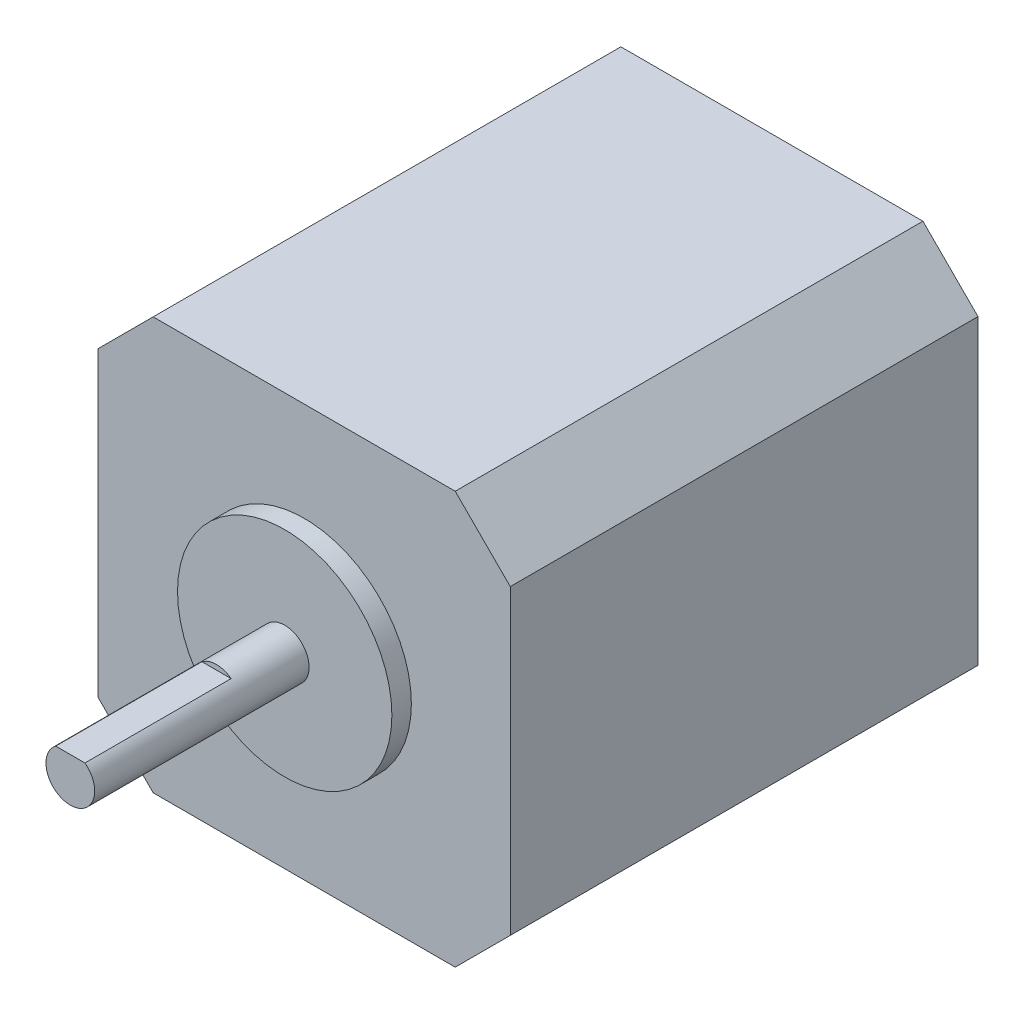
SolidWorks part; units mm, degrees
ref_plane "Front Plane" through (0, 0, 0) normal (0, 0, 1) x (1, 0, 0)
ref_plane "Top Plane" through (0, 0, 0) normal (0, 1, 0) x (1, 0, 0)
ref_plane "Right Plane" through (0, 0, 0) normal (1, 0, 0) x (0, 0, -1)
sketch "Sketch2" plane through (0, 0, 0) normal (0, 0, 1) x (1, 0, 0)
  line L1 (5.65, 0) -> (36.65, 0)
  line L2 (0, 5.65) -> (0, 36.65)
  line L3 (5.65, 42.3) -> (36.65, 42.3)
  line L4 (42.3, 5.65) -> (42.3, 36.65)
  line L5 (36.65, 0) -> (42.3, 5.65)
  line L6 (0, 5.65) -> (5.65, 0)
  line L7 (0, 36.65) -> (5.65, 42.3)
  line L8 (36.65, 42.3) -> (42.3, 36.65)
  point P0 (0, 0)
  point P1 (42.3, 42.3)
  point P2 (0, 42.3)
  point P3 (42.3, 0)
  point P11 (0, 0)
  dimension "D1" = 42.3
  dimension "D2" = 42.3
extrude "Boss-Extrude1" add sketch "Sketch2" along normal blind 48
sketch "Sketch3" plane through (0, 0, 48) normal (0, 0, 1) x (1, 0, 0)
  line L0 (0, 36.65) -> (0, 5.65) construction
  line L1 (5.65, 0) -> (36.65, 0) construction
  circle A0 centre (21.15, 21.15) radius 11
  dimension "D1" = 22
  dimension "D2" = 21.15
  dimension "D3" = 21.15
extrude "Boss-Extrude2" add sketch "Sketch3" along normal blind 2
sketch "Sketch4" plane through (0, 0, 50) normal (0, 0, 1) x (1, 0, 0)
  line L0 (5.65, 0) -> (36.65, 0) construction
  line L1 (42.3, 5.65) -> (42.3, 36.65) construction
  circle A0 centre (21.15, 21.15) radius 2.5
  dimension "D1" = 5
  dimension "D2" = 21.15
  dimension "D3" = 21.15
extrude "Boss-Extrude3" add sketch "Sketch4" along normal blind 22
sketch "Sketch5" plane through (0, 0, 72) normal (0, 0, 1) x (1, 0, 0)
  line L0 (21.15, 23.65) -> (21.15, 23.15)
  line L1 (21.15, 23.15) -> (17.955, 23.15)
  line L2 (17.955, 23.15) -> (17.955, 25.0585)
  line L3 (17.955, 25.0585) -> (25.206, 25.0585)
  line L4 (25.206, 25.0585) -> (25.206, 23.15)
  line L5 (25.206, 23.15) -> (17.955, 23.15)
  circle A0 centre (21.15, 21.15) radius 2.5 construction
  circle A1 centre (21.15, 21.15) radius 2.5 construction
  circle M2 centre (21.15, 21.15) radius 2.5
  dimension "D1" = 0.5
extrude "Cut-Extrude2" cut sketch "Sketch5" against normal blind 15 contours L5 L4 L3 L2 L1 M2 | L5 L0 M2 | L1 L0 M2
